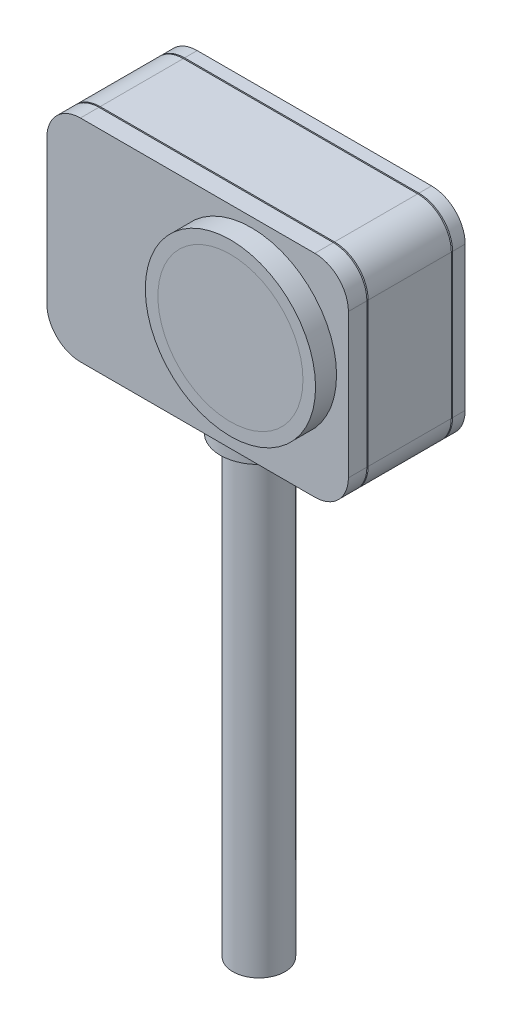
SolidWorks part; units mm, degrees
ref_plane "Front Plane" through (0, 0, 0) normal (0, 0, 1) x (1, 0, 0)
ref_plane "Top Plane" through (0, 0, 0) normal (0, 1, 0) x (1, 0, 0)
ref_plane "Right Plane" through (0, 0, 0) normal (1, 0, 0) x (0, 0, -1)
sketch "Sketch3" plane through (0, 0, 0) normal (0, 0, 1) x (1, 0, 0)
  line L1 (-27.9, 25.15) -> (27.9, 25.15)
  line L2 (-35.9, 17.15) -> (-35.9, -17.15)
  line L3 (-27.9, -25.15) -> (27.9, -25.15)
  line L4 (35.9, 17.15) -> (35.9, -17.15)
  line L5 (-35.9, 25.15) -> (35.9, -25.15) construction
  line L6 (-35.9, -25.15) -> (35.9, 25.15) construction
  arc A0 (35.9, 17.15) -> (27.9, 25.15) centre (27.9, 17.15) ccw
  arc A1 (27.9, -25.15) -> (35.9, -17.15) centre (27.9, -17.15) ccw
  arc A2 (-35.9, -17.15) -> (-27.9, -25.15) centre (-27.9, -17.15) ccw
  arc A3 (-27.9, 25.15) -> (-35.9, 17.15) centre (-27.9, 17.15) ccw
  point P0 (0, 0)
  dimension "D3" = 8
  dimension "D1" = 71.8
  dimension "D2" = 50.3
extrude "Boss-Extrude3" add sketch "Sketch3" along normal blind 3
sketch "Sketch4" plane through (0, 0, 3) normal (0, 0, 1) x (1, 0, 0)
  line L8 (27.9, 24.65) -> (-27.9, 24.65)
  line L9 (-35.4, 17.15) -> (-35.4, -17.15)
  line L10 (-27.9, -24.65) -> (27.9, -24.65)
  line L11 (35.4, -17.15) -> (35.4, 17.15)
  line L12 (27.9, 24.65) -> (-27.9, 24.65)
  line L13 (-35.4, 17.15) -> (-35.4, -17.15)
  line L14 (-27.9, -24.65) -> (27.9, -24.65)
  line L15 (35.4, -17.15) -> (35.4, 17.15)
  arc A8 (35.4, 17.15) -> (27.9, 24.65) centre (27.9, 17.15) ccw
  arc A9 (-27.9, 24.65) -> (-35.4, 17.15) centre (-27.9, 17.15) ccw
  arc A10 (-35.4, -17.15) -> (-27.9, -24.65) centre (-27.9, -17.15) ccw
  arc A11 (27.9, -24.65) -> (35.4, -17.15) centre (27.9, -17.15) ccw
  arc A12 (35.4, 17.15) -> (27.9, 24.65) centre (27.9, 17.15) ccw
  arc A13 (-27.9, 24.65) -> (-35.4, 17.15) centre (-27.9, 17.15) ccw
  arc A14 (-35.4, -17.15) -> (-27.9, -24.65) centre (-27.9, -17.15) ccw
  arc A15 (27.9, -24.65) -> (35.4, -17.15) centre (27.9, -17.15) ccw
  dimension "D1" = 0.5
extrude "Boss-Extrude4" add sketch "Sketch4" along normal blind 0.3
sketch "Sketch5" plane through (0, 0, 3.3) normal (0, 0, 1) x (1, 0, 0)
  line L8 (27.9, 25.15) -> (-27.9, 25.15)
  line L9 (-35.9, 17.15) -> (-35.9, -17.15)
  line L10 (-27.9, -25.15) -> (27.9, -25.15)
  line L11 (35.9, -17.15) -> (35.9, 17.15)
  line L12 (27.9, 25.15) -> (-27.9, 25.15)
  line L13 (-35.9, 17.15) -> (-35.9, -17.15)
  line L14 (-27.9, -25.15) -> (27.9, -25.15)
  line L15 (35.9, -17.15) -> (35.9, 17.15)
  arc A8 (35.9, 17.15) -> (27.9, 25.15) centre (27.9, 17.15) ccw
  arc A9 (-27.9, 25.15) -> (-35.9, 17.15) centre (-27.9, 17.15) ccw
  arc A10 (-35.9, -17.15) -> (-27.9, -25.15) centre (-27.9, -17.15) ccw
  arc A11 (27.9, -25.15) -> (35.9, -17.15) centre (27.9, -17.15) ccw
  arc A12 (35.9, 17.15) -> (27.9, 25.15) centre (27.9, 17.15) ccw
  arc A13 (-27.9, 25.15) -> (-35.9, 17.15) centre (-27.9, 17.15) ccw
  arc A14 (-35.9, -17.15) -> (-27.9, -25.15) centre (-27.9, -17.15) ccw
  arc A15 (27.9, -25.15) -> (35.9, -17.15) centre (27.9, -17.15) ccw
  dimension "D1" = 0.5
extrude "Boss-Extrude5" add sketch "Sketch5" along normal blind 19.8
sketch "Sketch6" plane through (0, 0, 23.1) normal (0, 0, 1) x (1, 0, 0)
  line L8 (27.9, 24.65) -> (-27.9, 24.65)
  line L9 (-35.4, 17.15) -> (-35.4, -17.15)
  line L10 (-27.9, -24.65) -> (27.9, -24.65)
  line L11 (35.4, -17.15) -> (35.4, 17.15)
  line L12 (27.9, 24.65) -> (-27.9, 24.65)
  line L13 (-35.4, 17.15) -> (-35.4, -17.15)
  line L14 (-27.9, -24.65) -> (27.9, -24.65)
  line L15 (35.4, -17.15) -> (35.4, 17.15)
  arc A8 (35.4, 17.15) -> (27.9, 24.65) centre (27.9, 17.15) ccw
  arc A9 (-27.9, 24.65) -> (-35.4, 17.15) centre (-27.9, 17.15) ccw
  arc A10 (-35.4, -17.15) -> (-27.9, -24.65) centre (-27.9, -17.15) ccw
  arc A11 (27.9, -24.65) -> (35.4, -17.15) centre (27.9, -17.15) ccw
  arc A12 (35.4, 17.15) -> (27.9, 24.65) centre (27.9, 17.15) ccw
  arc A13 (-27.9, 24.65) -> (-35.4, 17.15) centre (-27.9, 17.15) ccw
  arc A14 (-35.4, -17.15) -> (-27.9, -24.65) centre (-27.9, -17.15) ccw
  arc A15 (27.9, -24.65) -> (35.4, -17.15) centre (27.9, -17.15) ccw
  dimension "D1" = 0.5
extrude "Boss-Extrude6" add sketch "Sketch6" along normal blind 0.3
sketch "Sketch7" plane through (0, 0, 23.4) normal (0, 0, 1) x (1, 0, 0)
  line L8 (27.9, 25.15) -> (-27.9, 25.15)
  line L9 (-35.9, 17.15) -> (-35.9, -17.15)
  line L10 (-27.9, -25.15) -> (27.9, -25.15)
  line L11 (35.9, -17.15) -> (35.9, 17.15)
  line L12 (27.9, 25.15) -> (-27.9, 25.15)
  line L13 (-35.9, 17.15) -> (-35.9, -17.15)
  line L14 (-27.9, -25.15) -> (27.9, -25.15)
  line L15 (35.9, -17.15) -> (35.9, 17.15)
  arc A8 (35.9, 17.15) -> (27.9, 25.15) centre (27.9, 17.15) ccw
  arc A9 (-27.9, 25.15) -> (-35.9, 17.15) centre (-27.9, 17.15) ccw
  arc A10 (-35.9, -17.15) -> (-27.9, -25.15) centre (-27.9, -17.15) ccw
  arc A11 (27.9, -25.15) -> (35.9, -17.15) centre (27.9, -17.15) ccw
  arc A12 (35.9, 17.15) -> (27.9, 25.15) centre (27.9, 17.15) ccw
  arc A13 (-27.9, 25.15) -> (-35.9, 17.15) centre (-27.9, 17.15) ccw
  arc A14 (-35.9, -17.15) -> (-27.9, -25.15) centre (-27.9, -17.15) ccw
  arc A15 (27.9, -25.15) -> (35.9, -17.15) centre (27.9, -17.15) ccw
  dimension "D1" = 0.5
extrude "Boss-Extrude7" add sketch "Sketch7" along normal blind 4.4
sketch "Sketch19" plane through (0, -25.15, 0) normal (0, -1, 0) x (1, 0, 0)
  line L0 (-27.9, 13.2) -> (27.9, 13.2) construction
  line L1 (-27.9, 23.1) -> (-27.9, 3.3) construction
  line L2 (27.9, 23.1) -> (27.9, 3.3) construction
  line L3 (0, 3.3) -> (0, 23.1) construction
  line L4 (-27.9, 3.3) -> (27.9, 3.3) construction
  line L5 (-27.9, 23.1) -> (27.9, 23.1) construction
  circle A0 centre (0, 13.2) radius 9.2063
extrude "Boss-Extrude11" add sketch "Sketch19" along normal blind 8
sketch "Sketch20" plane through (0, -33.15, 0) normal (0, -1, 0) x (1, 0, 0)
  circle A0 centre (0, 13.2) radius 6.2063
  circle A1 centre (0, 13.2) radius 9.2063 construction
  dimension "D1" = 3
extrude "Boss-Extrude12" add sketch "Sketch20" along normal blind 108
sketch "Sketch21" plane through (0, 0, 27.8) normal (0, 0, 1) x (1, 0, 0)
  circle A1 centre (12.8115, 2.6286) radius 20.2691
extrude "Boss-Extrude13" add sketch "Sketch21" along normal blind 5
sketch "Sketch23" plane through (0, 0, 32.8) normal (0, 0, 1) x (1, 0, 0)
  circle A0 centre (12.8115, 2.6286) radius 17.2691
  circle A1 centre (12.8115, 2.6286) radius 20.2691 construction
  dimension "D1" = 3
extrude "Cut-Extrude2" cut sketch "Sketch23" against normal blind 1
sketch "Sketch24" plane through (0, 0, 31.8) normal (0, 0, 1) x (1, 0, 0)
  line L1 (4.7672, 12.62) -> (20.8558, 12.62)
  line L2 (-0.2328, 7.62) -> (-0.2328, -2.3628)
  line L3 (4.7672, -7.3628) -> (20.8558, -7.3628)
  line L4 (25.8558, 7.62) -> (25.8558, -2.3628)
  line L5 (-0.2328, 12.62) -> (25.8558, -7.3628) construction
  line L6 (-0.2328, -7.3628) -> (25.8558, 12.62) construction
  arc A0 (-0.2328, -2.3628) -> (4.7672, -7.3628) centre (4.7672, -2.3628) ccw
  arc A1 (20.8558, 12.62) -> (25.8558, 7.62) centre (20.8558, 7.62) cw
  arc A2 (25.8558, -2.3628) -> (20.8558, -7.3628) centre (20.8558, -2.3628) cw
  arc A3 (4.7672, 12.62) -> (-0.2328, 7.62) centre (4.7672, 7.62) ccw
  point P0 (12.8115, 2.6286)
  dimension "D1" = 5
extrude "Cut-Extrude3" cut sketch "Sketch24" against normal blind 1
sketch "Sketch25" plane through (0, 0, 30.8) normal (0, 0, 1) x (1, 0, 0)
  circle A0 centre (12.8115, 2.6286) radius 9.507
extrude "Cut-Extrude4" cut sketch "Sketch25" against normal blind 1
sketch "Sketch29" plane through (0, 0, 32.8) normal (0, 0, 1) x (1, 0, 0)
  circle A0 centre (12.8115, 2.6286) radius 17.2691 construction
  circle A1 centre (12.8115, 2.6286) radius 17.2691
extrude "Boss-Extrude14" add sketch "Sketch29" against normal blind 0.2 separate body
scale "Scale1" bodies to scale 126 125 scale about origin uniform scaling yes scale factor 0.278552
sketch "Sketch31" plane through (0, -39.3175, 0) normal (0, -1, 0) x (1, 0, 0)
  circle A0 centre (0, 3.6769) radius 0.75
  dimension "D1" = 1.5
extrude "Boss-Extrude15" add sketch "Sketch31" along normal blind 0.5
